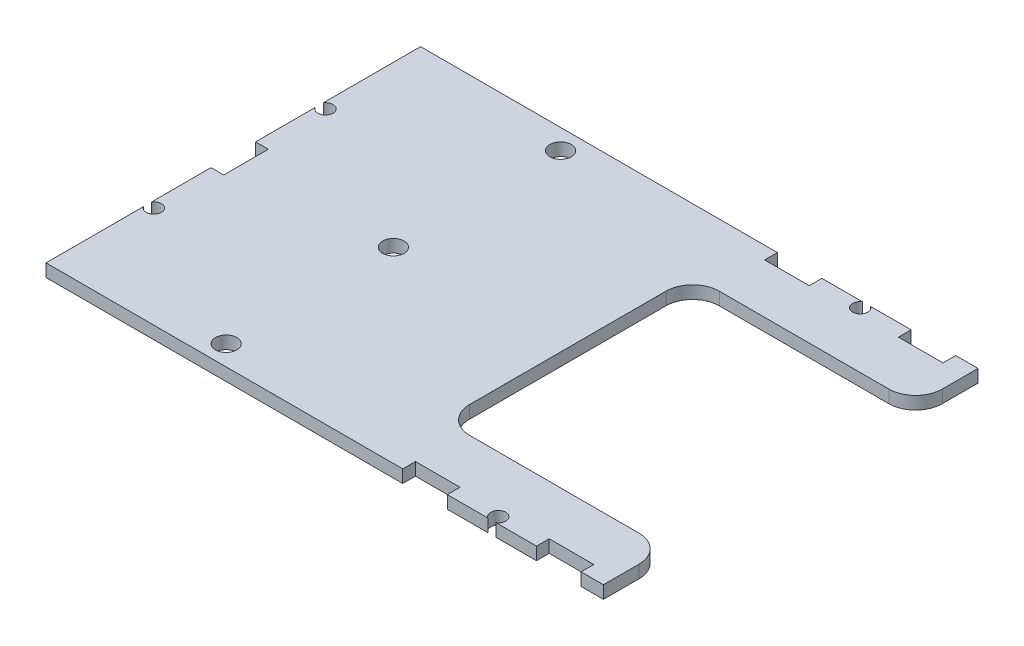
SolidWorks part; units mm, degrees
material "Pine"
ref_plane "Front" through (0, 0, 0) normal (0, 0, 1) x (1, 0, 0)
ref_plane "Top" through (0, 0, 0) normal (0, 1, 0) x (1, 0, 0)
ref_plane "Right" through (0, 0, 0) normal (1, 0, 0) x (0, 0, -1)
sketch "Sketch1" plane through (0, 0, 0) normal (0, 1, 0) x (1, 0, 0)
  line L1 (-62.5, 42) -> (62.5, 42)
  line L2 (-62.5, 42) -> (-62.5, -42)
  line L3 (-62.5, -42) -> (62.5, -42)
  line L4 (62.5, 42) -> (62.5, -42)
  line L5 (-62.5, 42) -> (62.5, -42) construction
  line L6 (-62.5, -42) -> (62.5, 42) construction
  point P0 (0, 0)
  dimension "D1" = 84
  dimension "D2" = 125
extrude "Boss-Extrude1" add sketch "Sketch1" along normal blind 2.85
sketch "Sketch2" plane through (0, 0, 0) normal (0, -1, 0) x (1, 0, 0)
  line L0 (62.5, 0) -> (44.5, 0) construction
  line L1 (62.5, 42) -> (62.5, -42) construction
  circle A0 centre (44.5, 0) radius 1.5
  dimension "D2" = 3
  dimension "D1" = 18
extrude "Cut-Extrude1" cut sketch "Sketch2" against normal through all
sketch "Sketch3" plane through (0, 2.85, 0) normal (0, 1, 0) x (1, 0, 0)
  line L0 (-26.6, 0) -> (0, 0) construction
  line L1 (-26.6, 0) -> (-26.6, 37.5) construction
  line L2 (-26.6, 0) -> (-26.6, -37.5) construction
  line L3 (-62.5, 42) -> (-62.5, -42) construction
  circle A0 centre (-26.6, 0) radius 2.4
  circle A1 centre (-26.6, 37.5) radius 2.4
  circle A2 centre (-26.6, -37.5) radius 2.4
  dimension "D1" = 4.8
  dimension "D2" = 75
  dimension "D3" = 35.9
extrude "Cut-Extrude2" cut sketch "Sketch3" against normal through all
sketch "Sketch4" plane through (0, 2.85, 0) normal (0, 1, 0) x (1, 0, 0)
  line L0 (-62.5, 42) -> (-62.5, -42) construction
  line L1 (-62.5, 5) -> (-59.65, 5)
  line L2 (-62.5, 5) -> (-62.5, -5)
  line L3 (-62.5, -5) -> (-59.65, -5)
  line L4 (-59.65, 5) -> (-59.65, -5)
  line L5 (-61.075, 19.25) -> (-61.075, 5) construction
  line L6 (-61.075, -5) -> (-61.075, -19.25) construction
  line L7 (-59.65, 0) -> (0, 0) construction
  line L8 (62.5, 42) -> (-62.5, 42) construction
  circle A0 centre (-61.075, -19.25) radius 1.7
  circle A1 centre (-61.075, 19.25) radius 1.7
  dimension "D3" = 3.4
  dimension "D1" = 10
  dimension "D2" = 2.85
  dimension "D4" = 22.75
extrude "Cut-Extrude3" cut sketch "Sketch4" against normal through all
sketch "Sketch5" plane through (0, 2.85, 0) normal (0, 1, 0) x (1, 0, 0)
  line L0 (62.5, 42) -> (-62.5, 42) construction
  line L1 (57.5, 42) -> (47.5, 42)
  line L2 (57.5, 42) -> (57.5, 39.15)
  line L3 (57.5, 39.15) -> (47.5, 39.15)
  line L4 (47.5, 42) -> (47.5, 39.15)
  line L5 (27.5, 40.575) -> (37.5, 40.575) construction
  line L6 (17.5, 42) -> (27.5, 42)
  line L7 (17.5, 42) -> (17.5, 39.15)
  line L8 (17.5, 39.15) -> (27.5, 39.15)
  line L9 (27.5, 42) -> (27.5, 39.15)
  line L10 (37.5, 40.575) -> (47.5, 40.575) construction
  line L11 (62.5, -42) -> (62.5, 42) construction
  circle A0 centre (37.5, 40.575) radius 1.7
  arc A1 (-62.5, 18.323) -> (-62.5, 20.177) centre (-61.075, 19.25) ccw construction
  dimension "D1" = 2.85
  dimension "D2" = 10
  dimension "D3" = 5
  dimension "D4" = 20
extrude "Cut-Extrude4" cut sketch "Sketch5" against normal through all
mirror "Mirror1" about plane through (0, 0, 0) normal (0, 0, 1) of "Cut-Extrude4"
sketch "Sketch6" plane through (0, 2.85, 0) normal (0, 1, 0) x (1, 0, 0)
  line L0 (62.5, -42) -> (62.5, 42) construction
  line L1 (62.5, 28) -> (12.5, 28)
  line L2 (62.5, 28) -> (62.5, -28)
  line L3 (62.5, -28) -> (12.5, -28)
  line L4 (12.5, 28) -> (12.5, -28)
  line L5 (12.5, 0) -> (0, 0) construction
  dimension "D1" = 50
  dimension "D2" = 56
extrude "Cut-Extrude5" cut sketch "Sketch6" against normal through all
fillet "Fillet1" radius 6 4 edges at (12.5, 1.425, 28) (62.5, 1.425, 28) (12.5, 1.425, -28) (62.5, 1.425, -28)
